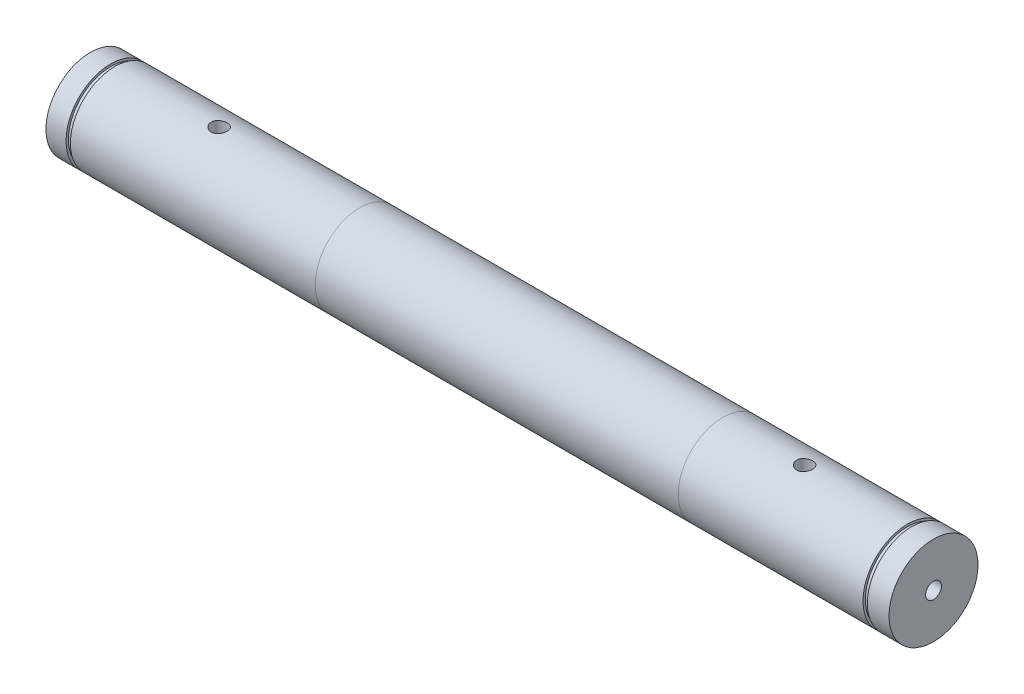
SolidWorks part; units mm, degrees
material "1.7225 (42CrMo4)"
ref_plane "E_Oben" through (0, 0, 0) normal (0, 0, 1) x (1, 0, 0)
ref_plane "E_Vorne" through (0, 0, 0) normal (0, 1, 0) x (1, 0, 0)
ref_plane "E_Rechts" through (0, 0, 0) normal (1, 0, 0) x (0, 0, -1)
ref_axis "A_Drehachse" through (-88.99, 0, 0) along (1, 0, 0)
sketch "Skizze1" plane through (0, 0, 0) normal (0, 0, 1) x (1, 0, 0)
  line L1 (0, -55) -> (0, 55) construction
  line L3 (180, 19) -> (180, 0)
  line L4 (180, 0) -> (-180, 0)
  line L7 (-180, 19) -> (-180, 0)
  line L10 (-65, 19) -> (-65, 27)
  line L11 (-65, 27) -> (-60, 27)
  line L12 (-60, 27) -> (-60, 19.0001)
  line L13 (-180, 19) -> (-65, 19)
  line L14 (-60, 19.0001) -> (90, 19.0001)
  line L15 (90, 19.0001) -> (90, 19)
  line L16 (90, 19) -> (180, 19)
  point P12 (0, 0)
  point P19 (-62.5, 27)
  dimension "D1" = 19.0001
  dimension "D2" = 19
  dimension "D3" = 19
  dimension "D4" = 360
  dimension "D5" = 115
  dimension "D6" = 5
  dimension "D7" = 27
  dimension "D8" = 150
revolve "Rotation1" add sketch "Skizze1" angle 360 about L4
hole_wizard "M8 Gewindebohrung1" positions "Skizze13" profile "Skizze14" tap size "M8" standard "DIN"
sketch "Skizze13" plane through (180, 0, 0) normal (1, 0, 0) x (0, 0, -1)
  point P0 (0, 0)
  point P3 (0, 0)
sketch "Skizze14" plane through (180, 0, 0) normal (0, 1, 0) x (0, 0, -1)
  line L0 (0, 0) -> (0, 327.0429)
  line L1 (0, 327.0429) -> (3.4, 325)
  line L2 (3.4, 325) -> (3.4, 0)
  line L5 (3.4, 0) -> (0, 0)
  line L10 (0, 327.0429) -> (-3.4, 325) construction
  line L11 (0, -6.35) -> (0, 107.95) construction
  dimension "Bohrerdurchmesser" = 6.8
  dimension "Bohrungstiefe" = 325
  dimension "Spitzenwinkel" = 118
cosmetic thread "Bohrungsgewinde2" parameters "D1"=20, "D2"=8
hole_wizard "M8 Gewindebohrung3" positions "Skizze17" profile "Skizze18" tap size "M8" standard "DIN"
sketch "Skizze17" plane through (0, 0, 0) normal (0, 1, 0) x (1, 0, 0)
  line L0 (-55, 0) -> (55, 0) construction
  line L1 (-88.99, 0) -> (88.99, 0) construction
  line L3 (180, -19) -> (180, 19) construction
  point P0 (-125, 0)
  point P4 (125, 0)
  dimension "D3" = 305
  dimension "D4" = 55
sketch "Skizze18" plane through (-125, 0, 0) normal (1, 0, 0) x (0, 0, -1)
  line L0 (0, 0) -> (0, 27)
  line L1 (0, 27) -> (3.4, 27)
  line L2 (3.4, 27) -> (3.4, 0)
  line L5 (3.4, 0) -> (0, 0)
  line L11 (0, -6.35) -> (0, 107.95) construction
  dimension "Bohrerdurchmesser" = 6.8
  dimension "Bohrungstiefe" = 27
mirror "Spiegeln2" about plane through (0, 0, 0) normal (0, 1, 0) of "M8 Gewindebohrung3"
sketch "Skizze19" plane through (0, 0, 0) normal (0, 0, 1) x (1, 0, 0)
  line L8 (180, 19) -> (128.4, 19) construction
  line L9 (168.9, 19) -> (170.75, 19)
  line L10 (168.9, 19) -> (168.9, 18)
  line L11 (168.9, 18) -> (170.75, 18)
  line L12 (170.75, 19) -> (170.75, 18)
  line L13 (180, -19) -> (180, 19) construction
  dimension "D1" = 9.25
  dimension "D2" = 1
  dimension "D4" = 1.85
revolve "Schnitt-Rotation1" cut sketch "Skizze19" angle 360 about axis through (-88.99, 0, 0) along (1, 0, 0)
sketch "Skizze20" plane through (0, 0, 0) normal (0, 0, 1) x (1, 0, 0)
  line L9 (-128.3999, 19) -> (-180, 19) construction
  line L10 (-180, 19) -> (-180, -19) construction
  line L11 (-171.4, 19) -> (-169.55, 19)
  line L12 (-171.4, 19) -> (-171.4, 18)
  line L13 (-171.4, 18) -> (-169.55, 18)
  line L14 (-169.55, 19) -> (-169.55, 18)
  dimension "D1" = 8.6
  dimension "D4" = 1
  dimension "D5" = 1.85
revolve "Schnitt-Rotation2" cut sketch "Skizze20" angle 360 about axis through (-88.99, 0, 0) along (1, 0, 0)
sketch "Sketch1" plane through (0, 0, 0) normal (0, 0, 1) x (1, 0, 0)
  line L0 (90, 19.0001) -> (-60, 19.0001) construction
  line L1 (-73.5073, 34.0844) -> (-52.0997, 34.0844)
  line L2 (-73.5073, 34.0844) -> (-73.5073, 19.0001)
  line L3 (-73.5073, 19.0001) -> (-52.0997, 19.0001)
  line L4 (-52.0997, 34.0844) -> (-52.0997, 19.0001)
  line L5 (180, -19) -> (180, 19) construction
  line L6 (-202.2322, 0) -> (240.1237, 0) construction
  dimension "D1" = 19.0001
  dimension "D2" = 21.4076
  dimension "D3" = 15.0843
  dimension "D4" = 232.0997
revolve "Cut-Revolve1" cut sketch "Sketch1" angle 360 about L6
